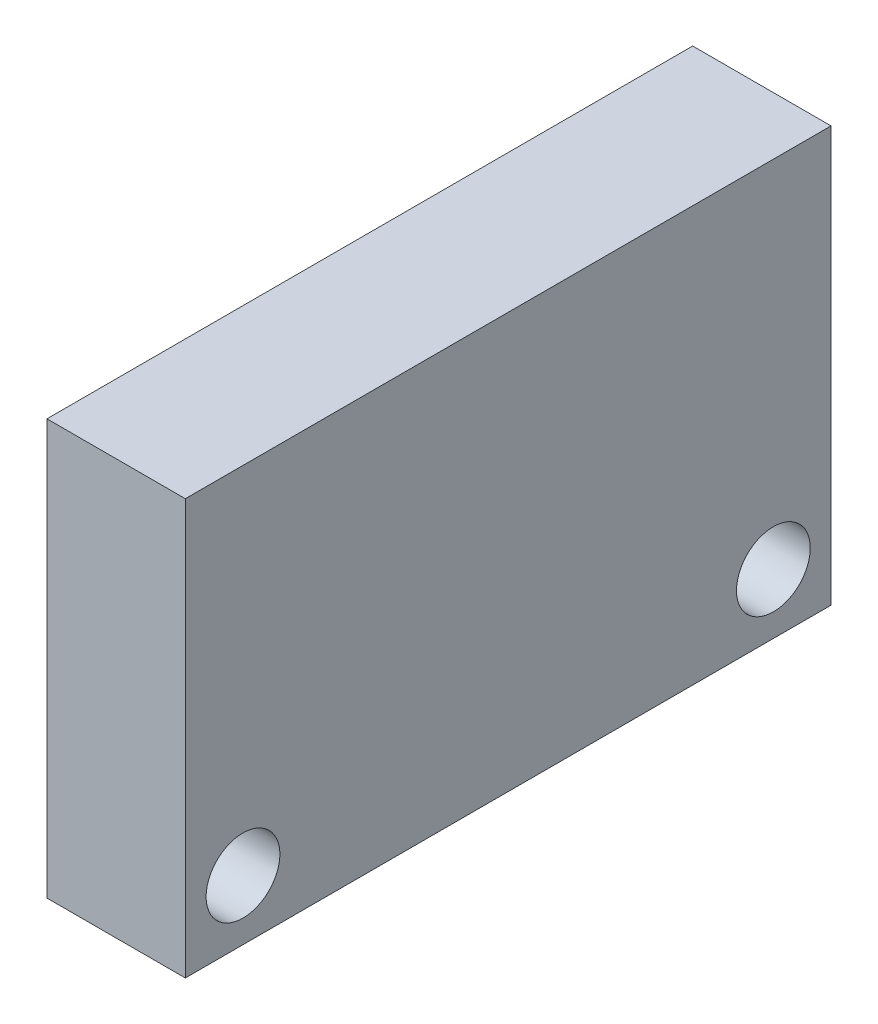
SolidWorks part; units mm, degrees
ref_plane "Plan de face" through (0, 0, 0) normal (0, 0, 1) x (1, 0, 0)
ref_plane "Plan de dessus" through (0, 0, 0) normal (0, 1, 0) x (1, 0, 0)
ref_plane "Plan de droite" through (0, 0, 0) normal (1, 0, 0) x (0, 0, -1)
sketch "Esquisse1" plane through (0, 0, 0) normal (0, 0, 1) x (1, 0, 0)
  line L1 (3, -9) -> (-3, -9)
  line L2 (3, -9) -> (3, 9)
  line L3 (3, 9) -> (-3, 9)
  line L4 (-3, -9) -> (-3, 9)
  line L5 (3, -9) -> (-3, 9) construction
  line L6 (3, 9) -> (-3, -9) construction
  point P0 (0, 0)
  dimension "D1" = 18
  dimension "D2" = 6
extrude "Boss.-Extru.1" add sketch "Esquisse1" along normal blind 28
sketch "Esquisse2" plane through (-3, 0, 0) normal (-1, 0, 0) x (0, 0, 1)
  line L0 (28, 9) -> (0, 9) construction
  line L1 (0, 9) -> (0, -9) construction
  line L2 (28, 9) -> (28, -9) construction
  circle A0 centre (2.5, -6.4) radius 1.6
  circle A1 centre (25.5, -6.4) radius 1.6
  dimension "D1" = 15.4
  dimension "D3" = 2.5
  dimension "D4" = 3.2
  dimension "D5" = 3.2
  dimension "D6" = 15.4
  dimension "D2" = 2.5
extrude "Enlèv. mat.-Extru.1" cut sketch "Esquisse2" against normal blind 28
